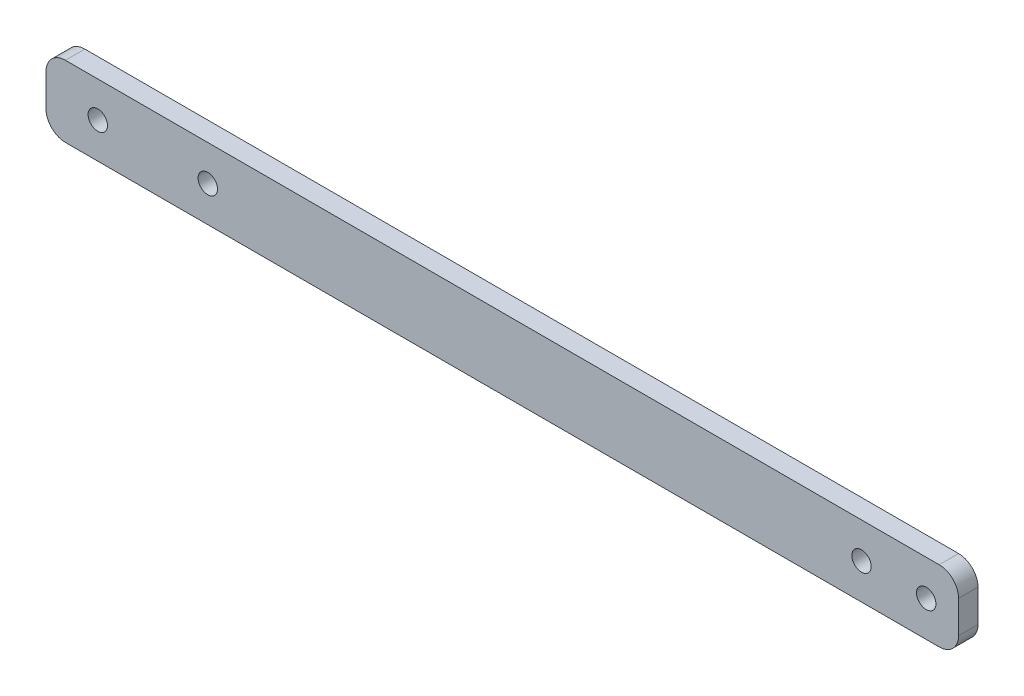
SolidWorks part; units mm, degrees
material "Thornel Mat VMA"
ref_plane "前视基准面" through (0, 0, 0) normal (0, 0, 1) x (1, 0, 0)
ref_plane "上视基准面" through (0, 0, 0) normal (0, 1, 0) x (1, 0, 0)
ref_plane "右视基准面" through (0, 0, 0) normal (1, 0, 0) x (0, 0, -1)
sketch "草图1" plane through (0, 0, 0) normal (0, 0, 1) x (1, 0, 0)
  line L1 (0, 0) -> (141, 0)
  line L2 (0, 0) -> (0, -11)
  line L3 (0, -11) -> (141, -11)
  line L4 (141, 0) -> (141, -11)
  circle A0 centre (126, -5.5) radius 1.5
  circle A1 centre (136, -5.5) radius 1.5
  circle A2 centre (8, -5.5) radius 1.5
  circle A3 centre (25, -5.5) radius 1.5
  point P13 (0, 0)
  dimension "D3" = 10
  dimension "D5" = 17
  dimension "D7" = 5.5
  dimension "D8" = 3
  dimension "D1" = 11
  dimension "D2" = 141
  dimension "D4" = 5
  dimension "D6" = 8
extrude "凸台-拉伸1" add sketch "草图1" along normal blind 3
fillet "圆角1" radius 3 4 edges at (141, -11, 1.5) (141, 0, 1.5) (0, -11, 1.5) (0, 0, 1.5)
